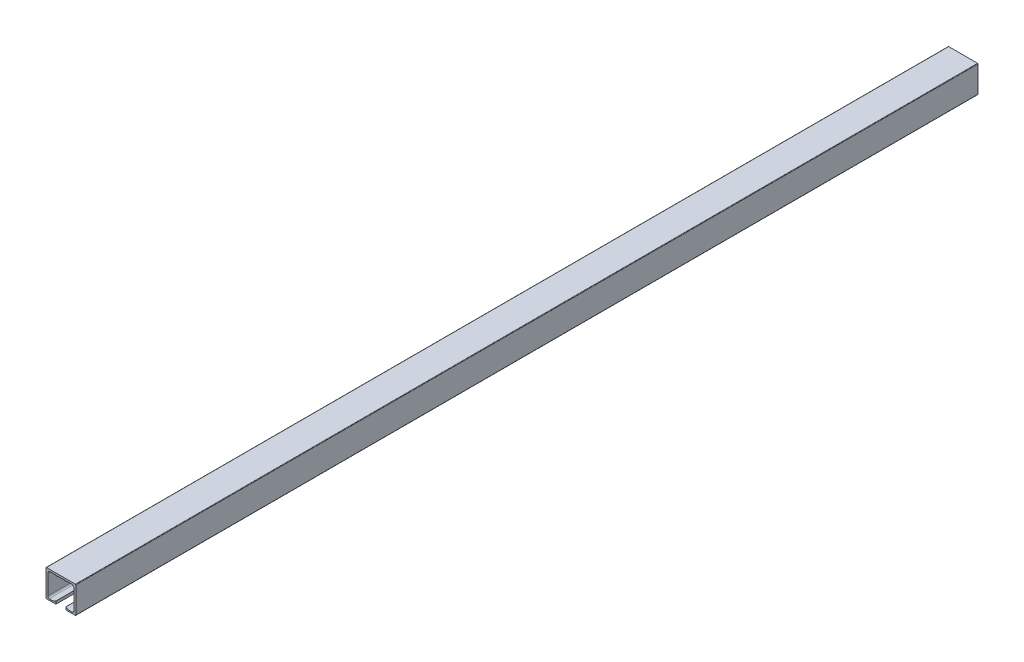
SolidWorks part; units mm, degrees
ref_plane "前视基准面" through (0, 0, 0) normal (0, 0, 1) x (1, 0, 0)
ref_plane "上视基准面" through (0, 0, 0) normal (0, 1, 0) x (1, 0, 0)
ref_plane "右视基准面" through (0, 0, 0) normal (1, 0, 0) x (0, 0, -1)
sketch "草图1" plane through (0, 0, 0) normal (0, 0, 1) x (1, 0, 0)
  line B0 (10.5, -30) -> (0, -30)
  line B1 (-0.5, -29.5) -> (-0.5, -0.5)
  line B2 (0, 0) -> (32, 0)
  line B3 (32.5, -0.5) -> (32.5, -29.5)
  line B4 (32, -30) -> (21.5, -30)
  line B5 (1.5, -26.4557) -> (1.5, -5)
  line B6 (4.5, -2) -> (10.4378, -2)
  line B7 (11.5622, -2) -> (20.4378, -2)
  line B8 (21.5622, -2) -> (27.5, -2)
  line B9 (30.5, -5) -> (30.5, -26.4557)
  line B10 (10.5, -30) -> (10.5, -27)
  line B11 (21.5, -30) -> (21.5, -27)
  line B12 (11.5622, -2) -> (11.1754, -2.7064)
  line B13 (10.4378, -2) -> (10.8246, -2.7064)
  line B14 (20.4378, -2) -> (20.8246, -2.7064)
  line B15 (21.5622, -2) -> (21.1754, -2.7064)
  arc B16 (-0.5, -29.5) -> (0, -30) centre (0, -29.5) ccw
  arc B17 (0, 0) -> (-0.5, -0.5) centre (0, -0.5) ccw
  arc B18 (32.5, -0.5) -> (32, 0) centre (32, -0.5) ccw
  arc B19 (32, -30) -> (32.5, -29.5) centre (32, -29.5) ccw
  arc B20 (4.5, -2) -> (1.5, -5) centre (4.5, -5) ccw
  arc B21 (30.5, -5) -> (27.5, -2) centre (27.5, -5) ccw
  arc B22 (3.1615, -28.4268) -> (10.5, -27) centre (4.9475, -18.0274) ccw
  arc B23 (1.5, -26.4557) -> (3.1615, -28.4268) centre (3.5, -26.4557) ccw
  arc B24 (21.5, -27) -> (28.8385, -28.4268) centre (27.0525, -18.0274) ccw
  arc B25 (28.8385, -28.4268) -> (30.5, -26.4557) centre (28.5, -26.4557) ccw
  arc B26 (10.8246, -2.7064) -> (11.1754, -2.7064) centre (11, -2.6104) ccw
  arc B27 (20.8246, -2.7064) -> (21.1754, -2.7064) centre (21, -2.6104) ccw
sketch_block_instance "A$C11707C52-1"
sketch_block "A$C11707C52"
extrude "凸台-拉伸1" add sketch "草图1" along normal blind 1000
